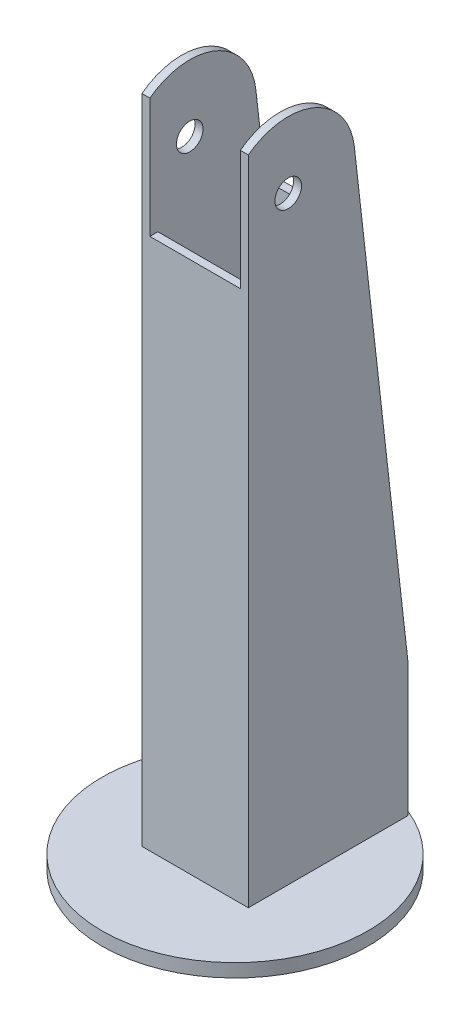
SolidWorks part; units mm, degrees
ref_plane "Alzado" through (0, 0, 0) normal (0, 0, 1) x (1, 0, 0)
ref_plane "Planta" through (0, 0, 0) normal (0, 1, 0) x (1, 0, 0)
ref_plane "Vista lateral" through (0, 0, 0) normal (1, 0, 0) x (0, 0, -1)
sketch "Croquis1" plane through (0, 0, 0) normal (0, 1, 0) x (1, 0, 0)
  line L1 (-20, -30) -> (20, -30)
  line L2 (-20, -30) -> (-20, 30)
  line L3 (-20, 30) -> (20, 30)
  line L4 (20, -30) -> (20, 30)
  line L5 (-20, -30) -> (20, 30) construction
  line L6 (-20, 30) -> (20, -30) construction
  point P0 (0, 0)
  dimension "D1" = 40
  dimension "D2" = 60
extrude "Saliente-Extruir1" add sketch "Croquis1" along normal blind 250
sketch "Croquis2" plane through (0, 250, 0) normal (0, 1, 0) x (1, 0, 0)
  line L0 (-20, -30) -> (20, -30) construction
  line L1 (-17, -30) -> (17, -30)
  line L2 (-17, -30) -> (-17, 30)
  line L3 (-17, 30) -> (17, 30)
  line L4 (17, -30) -> (17, 30)
  line L5 (20, 30) -> (-20, 30) construction
  line L6 (20, -30) -> (20, 30) construction
  line L7 (-20, 30) -> (-20, -30) construction
  dimension "D1" = 3
  dimension "D2" = 3
extrude "Cortar-Extruir1" cut sketch "Croquis2" against normal blind 50
sketch "Croquis3" plane through (20, 0, 0) normal (1, 0, 0) x (0, 0, -1)
  line L0 (-30, 250) -> (-30, 0) construction
  line L1 (-30, 250) -> (30, 250) construction
  circle A0 centre (-15, 225) radius 5
  dimension "D1" = 10
  dimension "D2" = 15
  dimension "D3" = 25
extrude "Cortar-Extruir2" cut sketch "Croquis3" against normal through all
sketch "Croquis5" plane through (20, 0, 0) normal (1, 0, 0) x (0, 0, -1)
  line L0 (30, 50) -> (9.8409, 227.8162)
  line L1 (30, 250) -> (30, 0) construction
  line L3 (-30, 0) -> (30, 0) construction
  line L4 (-30, 250) -> (-30, 0) construction
  arc A0 (9.8409, 227.8162) -> (-30, 245) centre (-15, 225) ccw
  circle A1 centre (-15, 225) radius 5 construction
  line M3 (-30, 250) -> (-30, 0)
  line M5 (30, 0) -> (30, 250)
  line M6 (30, 250) -> (-30, 250)
  dimension "D1" = 25
  dimension "D2" = 50
extrude "Cortar-Extruir5" cut sketch "Croquis5" against normal through all contours A0 L0 M5 M6 | A0 M6 M3
sketch "Croquis6" plane through (0, 0, 0) normal (0, -1, 0) x (1, 0, 0)
  line L0 (-20, 30) -> (20, 30) construction
  circle A0 centre (0, 15) radius 50
  point P4 (0, 30)
  dimension "D2" = 100
  dimension "D1" = 15
extrude "Saliente-Extruir2" add sketch "Croquis6" along normal blind 5
sketch "Croquis7" plane through (0, 200, 0) normal (0, 1, 0) x (1, 0, 0)
  line L0 (-17, 12.9944) -> (17, 12.9944) construction
  line L1 (17, -27) -> (-17, -27)
  line L2 (17, -27) -> (17, 9.9944)
  line L3 (17, 9.9944) -> (-17, 9.9944)
  line L4 (-17, -27) -> (-17, 9.9944)
  line L5 (-17, 12.9944) -> (-17, -30) construction
  line L6 (17, -30) -> (17, 12.9944) construction
  line L8 (-17, -30) -> (17, -30) construction
  dimension "D1" = 3
  dimension "D3" = 3
extrude "Cortar-Extruir6" cut sketch "Croquis7" against normal through all
